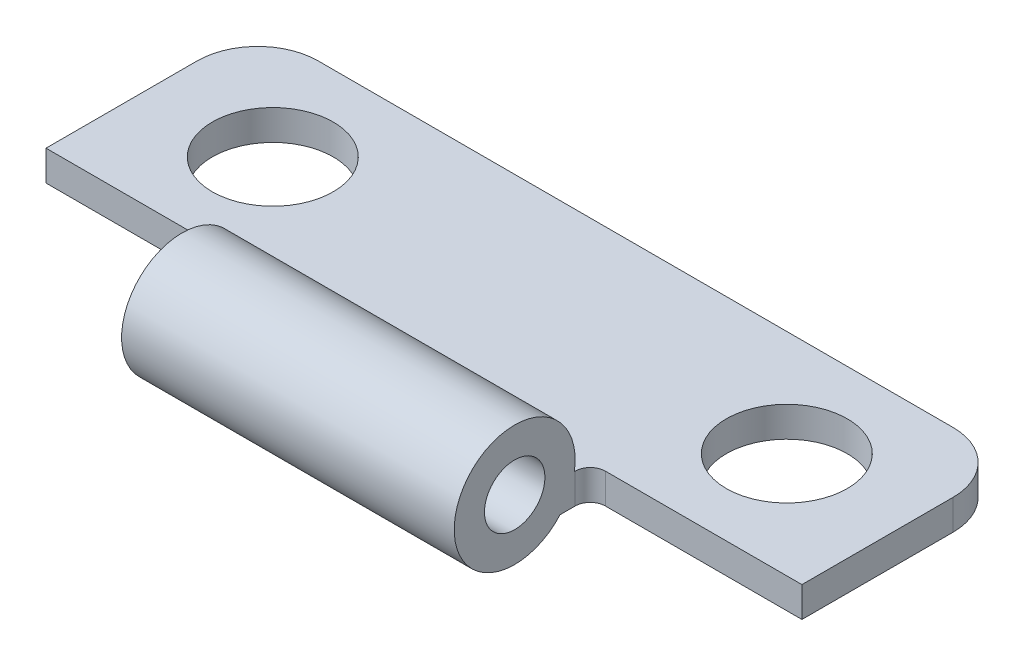
SolidWorks part; units mm, degrees
ref_plane "前视基准面" through (0, 0, 0) normal (0, 0, 1) x (1, 0, 0)
ref_plane "上视基准面" through (0, 0, 0) normal (0, 1, 0) x (1, 0, 0)
ref_plane "右视基准面" through (0, 0, 0) normal (1, 0, 0) x (0, 0, -1)
other "Configuration Table"
sketch "草图1" plane through (0, 0, 0) normal (0, 1, 0) x (1, 0, 0)
  line L0 (-12.5, 1) -> (-5.5, 1)
  line L1 (-12.5, 1) -> (-12.5, 8)
  line L2 (-12.5, 8) -> (12.5, 8)
  line L3 (12.5, 8) -> (12.5, 1)
  line L4 (-12.5, 4.5) -> (12.5, 4.5) construction
  line L5 (-5.5, 0) -> (5.5, 0)
  line L6 (5.5, 0) -> (5.5, 1)
  line L7 (-5.5, 0) -> (-5.5, 1)
  line L8 (5.5, 1) -> (12.5, 1)
  line L9 (0, 0) -> (0, 8) construction
  circle A0 centre (8.5, 4.5) radius 2
  circle A1 centre (-8.5, 4.5) radius 2
  dimension "D5" = 4
  dimension "D1" = 1
  dimension "D2" = 7
  dimension "D3" = 11
  dimension "D4" = 25
  dimension "D6" = 17
extrude "凸台-拉伸1" add sketch "草图1" along normal blind 1
fillet "圆角1" radius 2 2 edges at (-12.5, 0.5, -8) (12.5, 0.5, -8)
fillet "圆角2" radius 0.5 2 edges at (5.5, 0.5, -1) (-5.5, 0.5, -1)
sketch "草图3" plane through (0, 0, 0) normal (1, 0, 0) x (0, 0, -1)
  line L0 (1, 1) -> (1, 0) construction
  circle A0 centre (-1.5, 1.3229) radius 2
  circle A1 centre (-1.5, 1.3229) radius 1
  dimension "D1" = 4
  dimension "D2" = 2
  dimension "D3" = 2.5
extrude "凸台-拉伸2" add sketch "草图3" along normal mid plane 11
